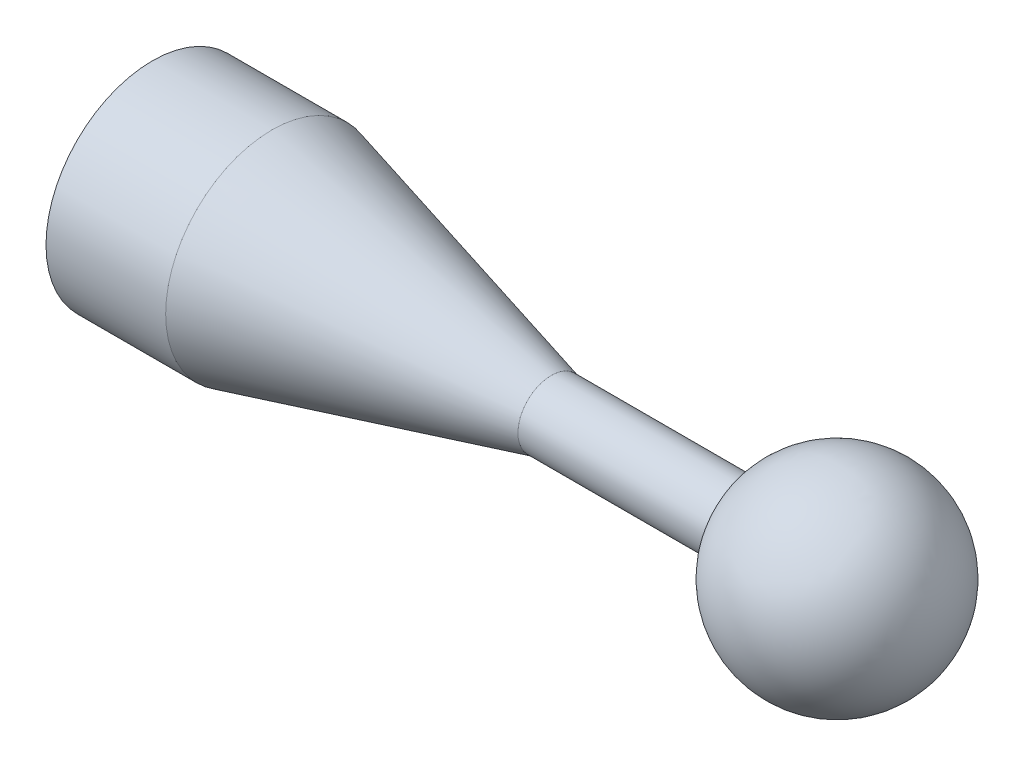
SolidWorks part; units mm, degrees
ref_plane "Plan de face" through (0, 0, 0) normal (0, 0, 1) x (1, 0, 0)
ref_plane "Plan de dessus" through (0, 0, 0) normal (0, 1, 0) x (1, 0, 0)
ref_plane "Plan de droite" through (0, 0, 0) normal (1, 0, 0) x (0, 0, -1)
sketch "Esquisse1" plane through (0, 0, 0) normal (0, 0, 1) x (1, 0, 0)
  line L0 (0, 0) -> (0, 16)
  line L1 (0, 16) -> (18, 16)
  line L2 (18, 16) -> (60, 5)
  line L3 (60, 5) -> (88.8579, 5)
  line L4 (-11.8977, 0) -> (129.4239, 0) construction
  line L5 (0, 0) -> (118, 0)
  arc A0 (118, 0) -> (88.8579, 5) centre (103, 0) ccw
  dimension "D6" = 15
  dimension "D1" = 16
  dimension "D2" = 18
  dimension "D3" = 42
  dimension "D4" = 5
  dimension "D5" = 103
revolve "Révolution1" add sketch "Esquisse1" angle 360 about L4
